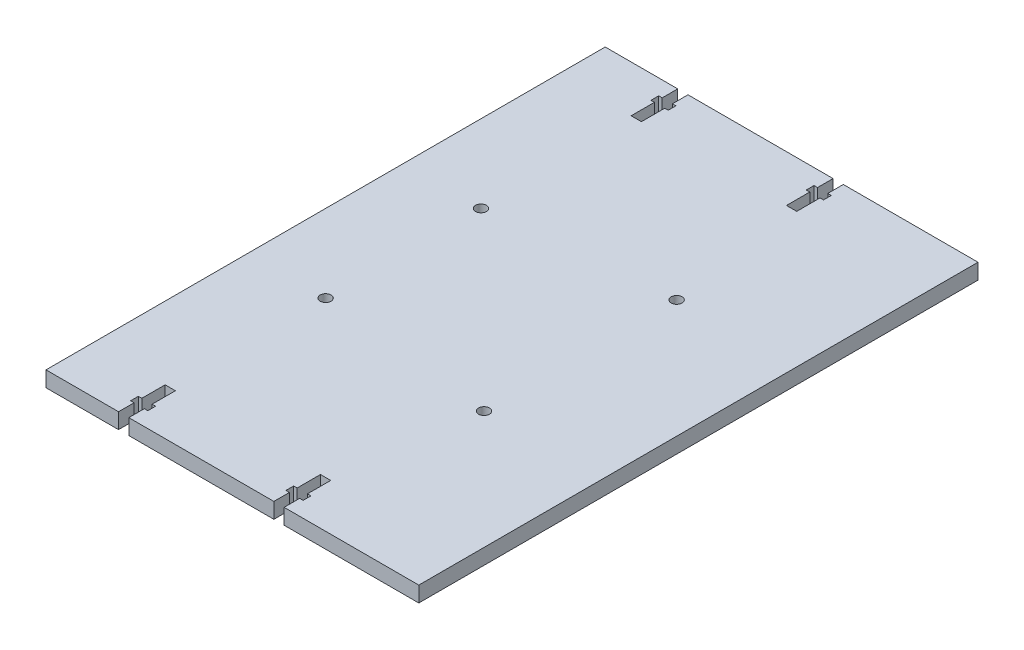
SolidWorks part; units mm, degrees
ref_plane "Front Plane" through (0, 0, 0) normal (0, 0, 1) x (1, 0, 0)
ref_plane "Top Plane" through (0, 0, 0) normal (0, 1, 0) x (1, 0, 0)
ref_plane "Right Plane" through (0, 0, 0) normal (1, 0, 0) x (0, 0, -1)
sketch "Sketch1" plane through (0, 0, 0) normal (0, 1, 0) x (1, 0, 0)
  line L1 (0, 0) -> (120, 0)
  line L2 (0, 0) -> (0, 180)
  line L3 (0, 180) -> (120, 180)
  line L4 (120, 0) -> (120, 180)
  dimension "D1" = 180
  dimension "D2" = 120
extrude "Boss-Extrude1" add sketch "Sketch1" along normal blind 5
sketch "Sketch2" plane through (0, 5, 0) normal (0, 1, 0) x (1, 0, 0)
  line L0 (0, 0) -> (120, 0) construction
  line L1 (23.35, 15) -> (26.65, 15)
  line L2 (23.35, 15) -> (23.35, 7.5)
  line L3 (23.35, 0) -> (26.65, 0)
  line L4 (26.65, 15) -> (26.65, 7.5)
  line L5 (26.65, 5) -> (27.775, 5)
  line L6 (22.225, 7.5) -> (23.35, 7.5)
  line L7 (22.225, 7.5) -> (22.225, 5)
  line L8 (22.225, 5) -> (23.35, 5)
  line L9 (27.775, 7.5) -> (27.775, 5)
  line L10 (26.65, 7.5) -> (27.775, 7.5)
  line L11 (23.35, 5) -> (23.35, 0)
  line L12 (26.65, 5) -> (26.65, 0)
  line L13 (25, 15) -> (25, 0) construction
  line L14 (0, 180) -> (0, 0) construction
  line L15 (-1000, 90) -> (49000, 90) construction
  line L16 (50, -819.8321) -> (50, 49174.3228) construction
  line L18 (76.65, 15) -> (76.65, 7.5)
  line L19 (77.775, 7.5) -> (76.65, 7.5)
  line L20 (77.775, 7.5) -> (77.775, 5)
  line L21 (77.775, 5) -> (76.65, 5)
  line L22 (76.65, 5) -> (76.65, 0)
  line L23 (76.65, 0) -> (73.35, 0)
  line L24 (73.35, 5) -> (73.35, 0)
  line L25 (73.35, 5) -> (72.225, 5)
  line L26 (72.225, 7.5) -> (72.225, 5)
  line L27 (73.35, 7.5) -> (72.225, 7.5)
  line L28 (73.35, 15) -> (73.35, 7.5)
  line L29 (76.65, 15) -> (73.35, 15)
  line L30 (76.65, 165) -> (73.35, 165)
  line L31 (73.35, 165) -> (73.35, 172.5)
  line L32 (73.35, 172.5) -> (72.225, 172.5)
  line L33 (72.225, 172.5) -> (72.225, 175)
  line L34 (73.35, 175) -> (72.225, 175)
  line L35 (73.35, 175) -> (73.35, 180)
  line L36 (76.65, 180) -> (73.35, 180)
  line L37 (76.65, 175) -> (76.65, 180)
  line L38 (77.775, 175) -> (76.65, 175)
  line L39 (77.775, 172.5) -> (77.775, 175)
  line L40 (77.775, 172.5) -> (76.65, 172.5)
  line L41 (76.65, 165) -> (76.65, 172.5)
  line L42 (23.35, 165) -> (23.35, 172.5)
  line L43 (22.225, 172.5) -> (23.35, 172.5)
  line L44 (22.225, 172.5) -> (22.225, 175)
  line L45 (22.225, 175) -> (23.35, 175)
  line L46 (23.35, 175) -> (23.35, 180)
  line L47 (23.35, 180) -> (26.65, 180)
  line L48 (26.65, 175) -> (26.65, 180)
  line L49 (26.65, 175) -> (27.775, 175)
  line L50 (27.775, 172.5) -> (27.775, 175)
  line L51 (26.65, 172.5) -> (27.775, 172.5)
  line L52 (26.65, 165) -> (26.65, 172.5)
  line L53 (23.35, 165) -> (26.65, 165)
  point P10 (22.225, 6.25)
  point P28 (0, 90)
  dimension "D1" = 15
  dimension "D2" = 3.3
  dimension "D3" = 5.55
  dimension "D4" = 2.5
  dimension "D5" = 5
  dimension "D6" = 5.55
  dimension "D7" = 25
  dimension "D8" = 50
extrude "Cut-Extrude1" cut sketch "Sketch2" against normal blind 5
sketch "Sketch3" plane through (0, 5, 0) normal (0, 1, 0) x (1, 0, 0)
  line L0 (82, 121) -> (82, 59) construction
  line L1 (25, 115) -> (25, 65) construction
  line L2 (0, 180) -> (0, 0) construction
  circle A0 centre (25, 65) radius 1.75
  circle A1 centre (82, 59) radius 1.75
  circle A2 centre (25, 115) radius 1.75
  circle A3 centre (82, 121) radius 1.75
  point P4 (25.211, 54.3499)
  point P7 (25, 90)
  point P10 (82, 90)
  point P11 (21.3589, 62.0766)
  point P14 (0, 90)
  dimension "D1" = 3.5
  dimension "D4" = 50
  dimension "D5" = 62
  dimension "D2" = 25
  dimension "D3" = 57
extrude "Cut-Extrude2" cut sketch "Sketch3" against normal blind 5
